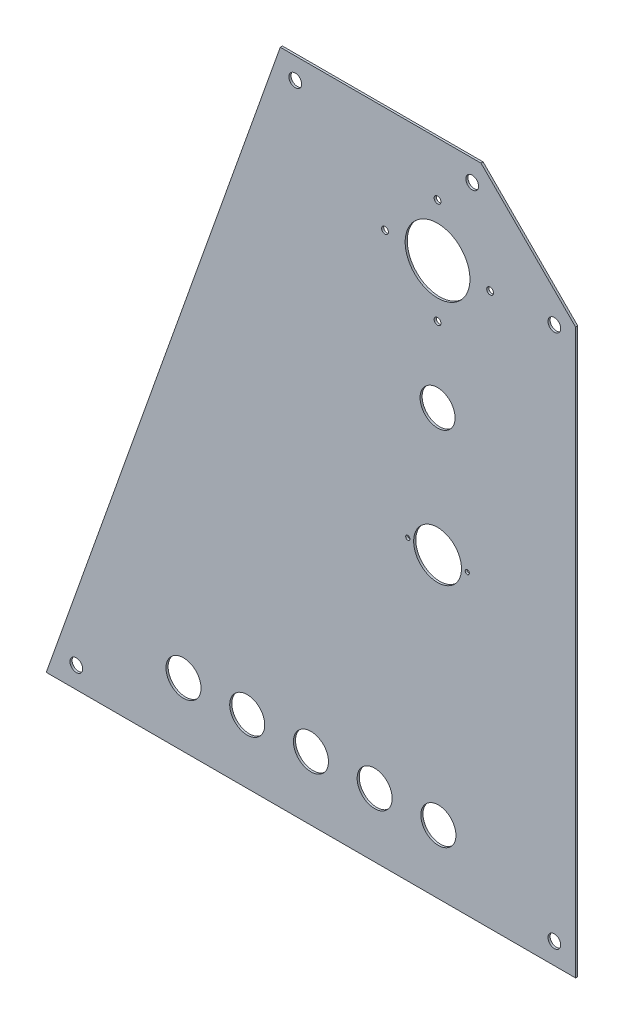
SolidWorks part; units mm, degrees
ref_plane "Front Plane" through (0, 0, 0) normal (1, 0, 0) x (0, 1, 0)
ref_plane "Top Plane" through (0, 0, 0) normal (0, 0, 1) x (0, 1, 0)
ref_plane "Right Plane" through (0, 0, 0) normal (0, 1, 0) x (-1, 0, 0)
sketch "Sketch1" plane through (0, 0, 0) normal (0, 0, 1) x (0, 1, 0)
  line L1 (-155, -125) -> (155, -125)
  line L2 (-155, -125) -> (-155, 125)
  line L3 (-155, 125) -> (155, 125)
  line L4 (155, -125) -> (155, 125)
  line L5 (-155, -125) -> (155, 125) construction
  line L6 (-155, 125) -> (155, -125) construction
  point P0 (0, 0)
  dimension "D1" = 310
  dimension "D2" = 250
extrude "Boss-Extrude1" add sketch "Sketch1" along normal blind 1
sketch "Sketch2" plane through (0, 0, 1) normal (0, 0, 1) x (0, -1, 0)
  line L0 (-155, -14.0477) -> (155, -124.2339)
  line L1 (-155, 125) -> (-155, -125) construction
  line L4 (155, -124.2339) -> (155, 125)
  line L5 (155, 125) -> (-110.4523, 125)
  line L6 (155, 125) -> (-155, 125) construction
  line L7 (-110.4523, 125) -> (-155, 80.4523)
  line L8 (-155, 80.4523) -> (-155, -14.0477)
  line L9 (-155, 80.4523) -> (-155, 125) construction
  line L10 (-155, 125) -> (-110.4523, 125) construction
  dimension "D1" = 63
  dimension "D2" = 329
  dimension "D3" = 94.5
extrude "Cut-Extrude1" cut sketch "Sketch2" against normal through all flip side to cut
sketch "Sketch3" plane through (0, 0, 1) normal (0, 0, 1) x (0, -1, 0)
  line L0 (-155, 60) -> (155, 60) construction
  line L2 (155, -124.2339) -> (155, 125) construction
  line L3 (155, 125) -> (-110.4523, 125) construction
  line L4 (-155, 80.4523) -> (-155, -14.0477) construction
  line L5 (-155, 60) -> (-105, 60) construction
  line L6 (-105, 60) -> (-105, 125) construction
  line L7 (-105, 35.2513) -> (-80.2513, 60) construction
  line L8 (-80.2513, 60) -> (-105, 84.7487) construction
  line L9 (-105, 84.7487) -> (-129.7487, 60) construction
  line L10 (-129.7487, 60) -> (-105, 35.2513) construction
  line L11 (15, 46) -> (15, 74) construction
  circle A0 centre (-105, 60) radius 15.25
  circle A1 centre (-45, 60) radius 8.25
  circle A2 centre (15, 60) radius 11.25
  circle A3 centre (-105, 35.2513) radius 1.6
  circle A4 centre (-129.7487, 60) radius 1.6
  circle A5 centre (-105, 84.7487) radius 1.6
  circle A6 centre (-80.2513, 60) radius 1.6
  circle A7 centre (15, 74) radius 1
  circle A8 centre (15, 46) radius 1
  circle A9 centre (15, 60) radius 14 construction
  dimension "D2" = 30.5
  dimension "D1" = 16.5
  dimension "D3" = 22.5
  dimension "D8" = 3.2
  dimension "D11" = 28
  dimension "D12" = 2
  dimension "D4" = 60
  dimension "D5" = 60
  dimension "D6" = 90
  dimension "D7" = 35
  dimension "D9" = 65
  dimension "D10" = 50
extrude "Cut-Extrude2" cut sketch "Sketch3" against normal through all
sketch "Sketch4" plane through (0, 0, 1) normal (0, 0, 1) x (0, -1, 0)
  line L0 (125, -113.5708) -> (125, 125) construction
  line L1 (-155, -14.0477) -> (155, -124.2339) construction
  line L2 (155, 125) -> (-110.4523, 125) construction
  line L3 (155, -124.2339) -> (155, 125) construction
  circle A0 centre (125, -59.617) radius 8.25
  circle A1 centre (125, -29.617) radius 8.25
  circle A2 centre (125, 0.383) radius 8.25
  circle A3 centre (125, 30.383) radius 8.25
  circle A4 centre (125, 60.383) radius 8.25
  point P22 (155, 0.383)
  dimension "D2" = 16.5
  dimension "D3" = 30
  dimension "D4" = 30
  dimension "D5" = 30
  dimension "D6" = 30
  dimension "D1" = 30
extrude "Cut-Extrude3" cut sketch "Sketch4" against normal through all
sketch "Sketch5" plane through (0, 0, 1) normal (0, 0, 1) x (0, -1, 0)
  line L0 (155, -124.2339) -> (155, 125) construction
  line L3 (155, 125) -> (-110.4523, 125) construction
  line L4 (-155, 80.4523) -> (-155, -14.0477) construction
  line L5 (-155, -14.0477) -> (155, -124.2339) construction
  line L6 (-110.4523, 125) -> (-155, 80.4523) construction
  circle A0 centre (145, -110.0666) radius 3
  circle A1 centre (-145, -6.9892) radius 3
  circle A2 centre (-145, 76.3101) radius 3
  circle A3 centre (145, 115) radius 3
  circle A4 centre (-106.3101, 115) radius 3
  dimension "D1" = 6
  dimension "D2" = 10
  dimension "D3" = 10
  dimension "D4" = 10
  dimension "D5" = 10
  dimension "D6" = 10
  dimension "D7" = 10
  dimension "D8" = 10
  dimension "D9" = 10
  dimension "D10" = 10
  dimension "D11" = 10
extrude "Cut-Extrude4" cut sketch "Sketch5" against normal through all
